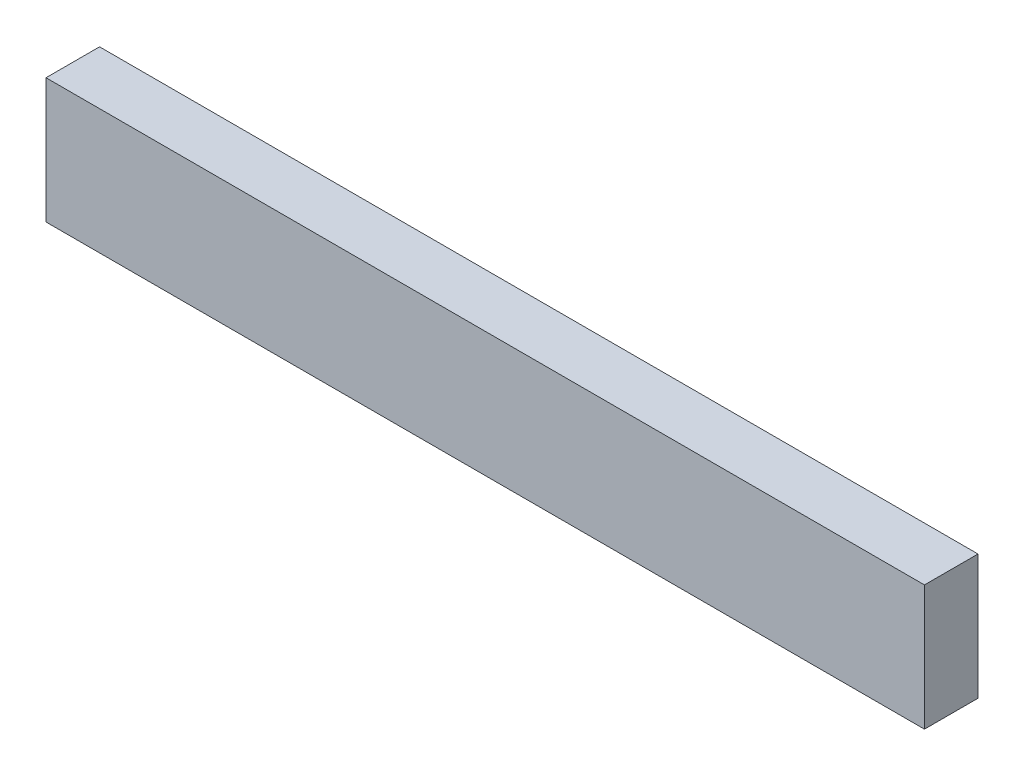
SolidWorks part; units mm, degrees
ref_plane "Front Plane" through (0, 0, 0) normal (0, 0, 1) x (1, 0, 0)
ref_plane "Top Plane" through (0, 0, 0) normal (0, 1, 0) x (1, 0, 0)
ref_plane "Right Plane" through (0, 0, 0) normal (1, 0, 0) x (0, 0, -1)
sketch "Sketch1" plane through (0, 0, 0) normal (0, 0, 1) x (1, 0, 0)
  line L0 (0, 0) -> (625, 0)
  line L1 (625, 0) -> (625, 88.9)
  line L2 (625, 88.9) -> (0, 88.9)
  line L3 (0, 88.9) -> (0, 0)
  point P6 (0, 0)
  point P7 (0, 0)
  dimension "D4" = 625
  dimension "D5" = 88.9
extrude "Boss-Extrude1" add sketch "Sketch1" along normal blind 38.1
